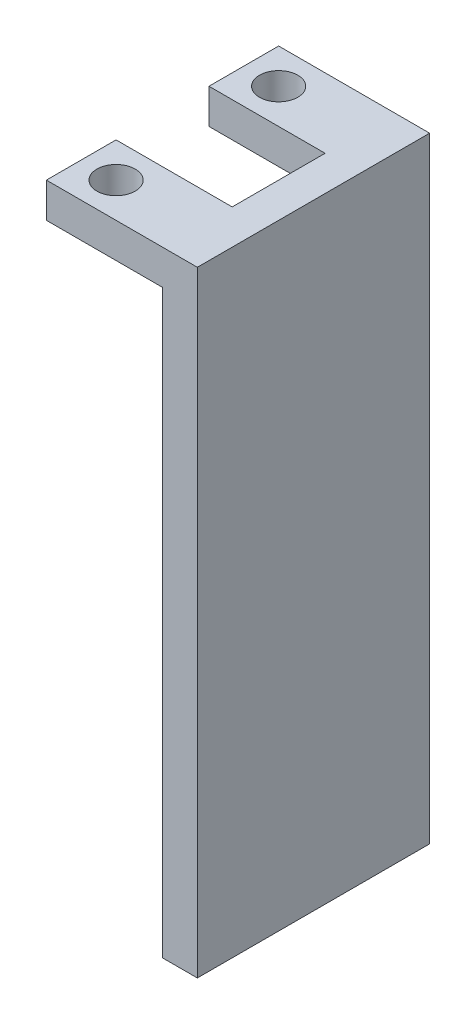
SolidWorks part; units mm, degrees
ref_plane "Plano frontal" through (0, 0, 0) normal (0, 0, 1) x (1, 0, 0)
ref_plane "Plano superior" through (0, 0, 0) normal (0, 1, 0) x (1, 0, 0)
ref_plane "Plano direito" through (0, 0, 0) normal (1, 0, 0) x (0, 0, -1)
sketch "Sketch1" plane through (0, 0, 0) normal (1, 0, 0) x (0, 0, -1)
  line L1 (-10, -26.5) -> (10, -26.5)
  line L2 (-10, -26.5) -> (-10, 26.5)
  line L3 (-10, 26.5) -> (10, 26.5)
  line L4 (10, -26.5) -> (10, 26.5)
  line L5 (-10, -26.5) -> (10, 26.5) construction
  line L6 (-10, 26.5) -> (10, -26.5) construction
  point P0 (0, 0)
  dimension "D1" = 53
  dimension "D2" = 20
extrude "Boss-Extrude1" add sketch "Sketch1" along normal blind 3 contours L2 L3 L4 L1
sketch "Sketch2" plane through (0, 0, 0) normal (-1, 0, 0) x (0, 0, 1)
  line L0 (10, -26.5) -> (10, 26.5) construction
  line L1 (-10, 26.5) -> (10, 26.5)
  line L2 (-10, 26.5) -> (-10, 23.5)
  line L3 (-10, 23.5) -> (10, 23.5)
  line L4 (10, 26.5) -> (10, 23.5)
  line L6 (-10, 26.5) -> (-4, 26.5)
  line L7 (-10, 26.5) -> (-10, 23.5)
  line L8 (-10, 23.5) -> (-4, 23.5)
  line L9 (-4, 26.5) -> (-4, 23.5)
  line L10 (10, 26.5) -> (4, 26.5)
  line L11 (10, 26.5) -> (10, 23.5)
  line L12 (10, 23.5) -> (4, 23.5)
  line L13 (4, 26.5) -> (4, 23.5)
  line M8 (10, -26.5) -> (10, 26.5)
  line M9 (10, 26.5) -> (-10, 26.5)
  line M10 (-10, 26.5) -> (-10, -26.5)
  dimension "D1" = 3
  dimension "D2" = 6
  dimension "D3" = 6
extrude "Boss-Extrude2" add sketch "Sketch2" along normal blind 10 contours L9 L1 L3 M10 | L13 L3 M9 M8
sketch "Sketch4" plane through (0, 23.5, 0) normal (0, -1, 0) x (1, 0, 0)
  line L1 (-10, 4) -> (-10, 10) construction
  line L2 (-10, -10) -> (-10, -4) construction
  circle A0 centre (-7, 7) radius 1.65
  circle A1 centre (-7, -7) radius 1.65
  point P4 (0, 0)
  point P8 (0, 0)
  point P11 (-10, 7)
  point P14 (-10, -7)
  point P15 (0, 0)
  dimension "D1" = 3.3
  dimension "D2" = 3.3
  dimension "D3" = 3
extrude "Cut-Extrude1" cut sketch "Sketch4" against normal up to next
equation "\"D2@Sketch4\"=\"D1@Sketch4\""
